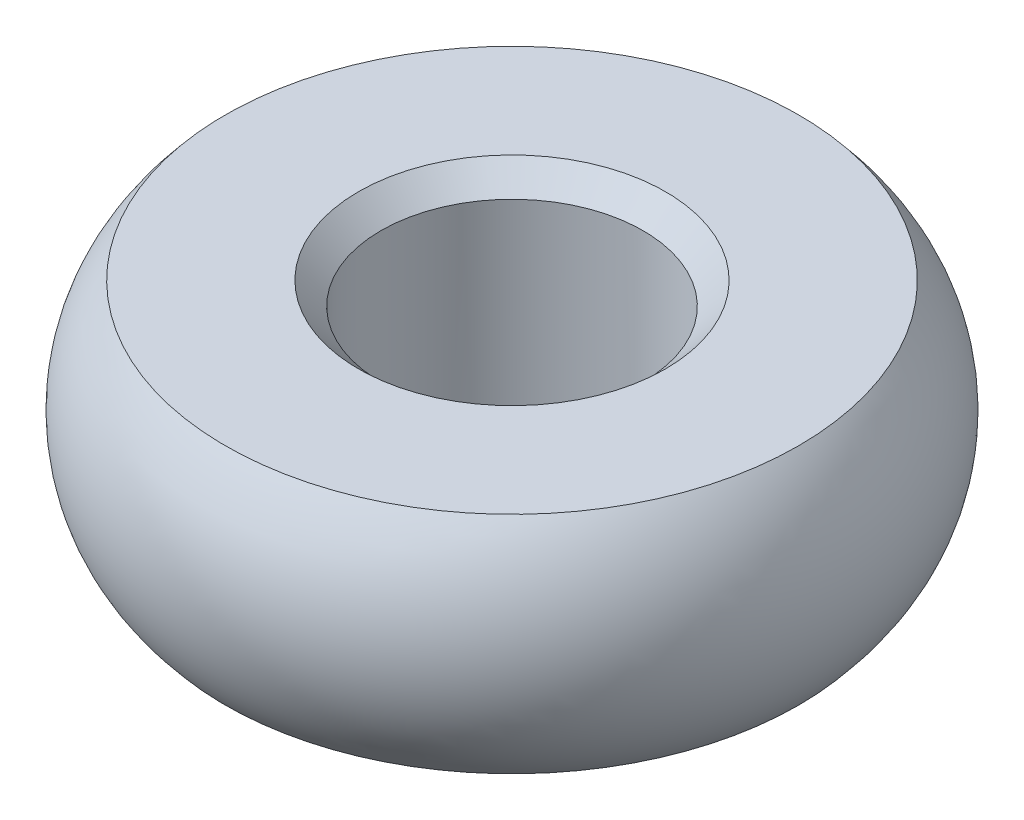
SolidWorks part; units mm, degrees
material "Custom Plastic"
ref_plane "Front Plane" through (0, 0, 0) normal (0, 0, 1) x (1, 0, 0)
ref_plane "Top Plane" through (0, 0, 0) normal (0, 1, 0) x (1, 0, 0)
ref_plane "Right Plane" through (0, 0, 0) normal (1, 0, 0) x (0, 0, -1)
sketch "Sketch1" plane through (0, 0, 0) normal (0, 0, 1) x (1, 0, 0)
  line L0 (0, -562.8227) -> (0, 27578.3136) construction
  line L1 (17.5, 15) -> (17.5, -15)
  line L2 (17.5, -15) -> (38.2705, -15)
  line L3 (17.5, 15) -> (38.2705, 15)
  arc A0 (38.2705, 15) -> (38.2705, -15) centre (21.5, 0) cw
  point P5 (17.5, 0)
  point P9 (44, 0)
  dimension "D3" = 22.5
  dimension "D1" = 30
  dimension "D2" = 17.5
  dimension "D4" = 88
revolve "Revolve1" add sketch "Sketch1" angle 360 about L0
chamfer "Chamfer1" distance 3 angle 45 2 edges at (17.5, 15, 0) (17.5, -15, 0)
